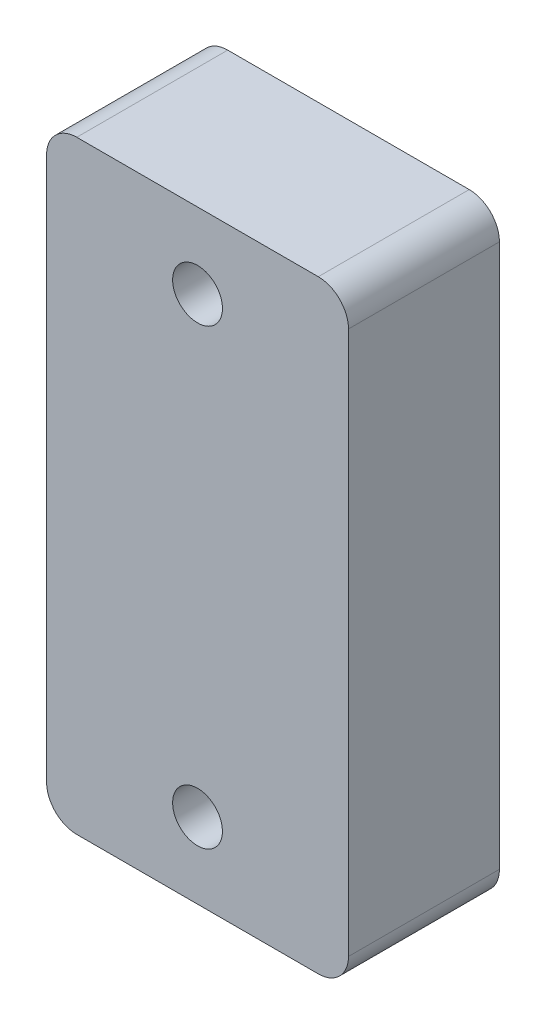
SolidWorks part; units mm, degrees
material "PLA"
ref_plane "前视基准面" through (0, 0, 0) normal (0, 0, 1) x (1, 0, 0)
ref_plane "上视基准面" through (0, 0, 0) normal (0, 1, 0) x (1, 0, 0)
ref_plane "右视基准面" through (0, 0, 0) normal (1, 0, 0) x (0, 0, -1)
other "Configuration Table"
sketch "草图1" plane through (0, 0, 0) normal (0, 0, 1) x (1, 0, 0)
  line L0 (0, 0) -> (-32.6503, 0) construction
  line L1 (-10, 20) -> (10, 20)
  line L2 (-10, 20) -> (-10, -20)
  line L3 (-10, -20) -> (10, -20)
  line L4 (10, 20) -> (10, -20)
  line L5 (-10, 20) -> (10, -20) construction
  line L6 (-10, -20) -> (10, 20) construction
  circle A0 centre (0, 15) radius 1.65
  circle A1 centre (0, -15) radius 1.65
  point P0 (0, 0)
  dimension "D3" = 3.3
  dimension "D4" = 30
  dimension "D1" = 40
  dimension "D2" = 20
extrude "凸台-拉伸1" add sketch "草图1" along normal blind 10
fillet "圆角1" radius 2 4 edges at (10, -20, 5) (-10, -20, 5) (-10, 20, 5) (10, 20, 5)
